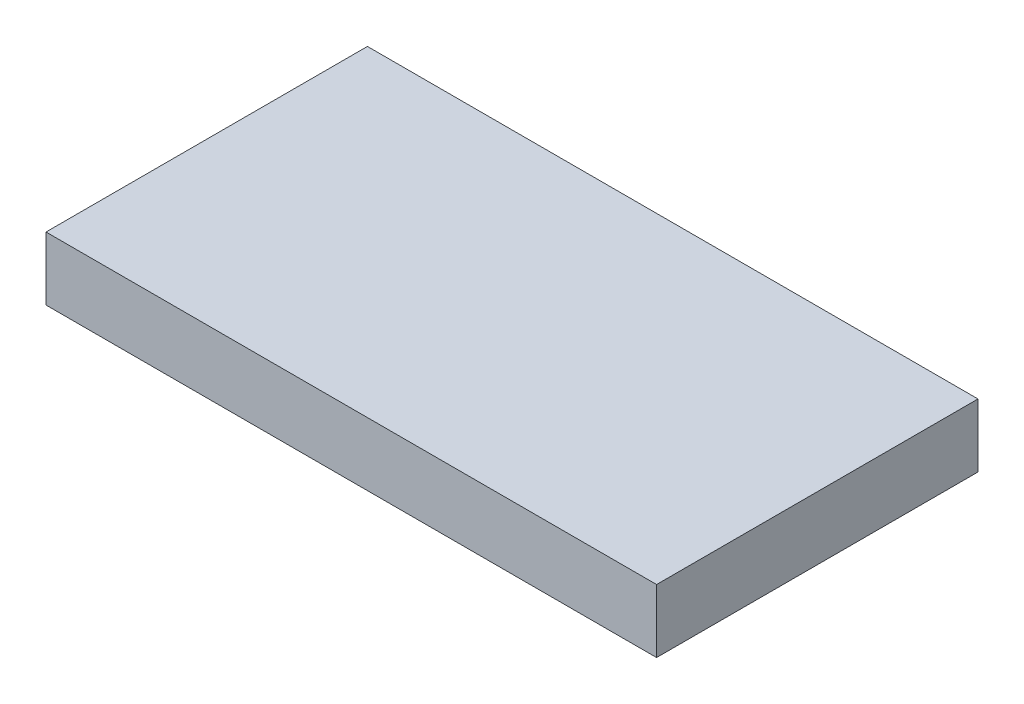
SolidWorks part; units mm, degrees
ref_plane "Front Plane" through (0, 0, 0) normal (0, 0, 1) x (1, 0, 0)
ref_plane "Top Plane" through (0, 0, 0) normal (0, 1, 0) x (1, 0, 0)
ref_plane "Right Plane" through (0, 0, 0) normal (1, 0, 0) x (0, 0, -1)
sketch "Sketch1" plane through (0, 0, 0) normal (0, 1, 0) x (1, 0, 0)
  line L1 (-482.5, 254) -> (482.5, 254)
  line L2 (-482.5, 254) -> (-482.5, -254)
  line L3 (-482.5, -254) -> (482.5, -254)
  line L4 (482.5, 254) -> (482.5, -254)
  line L5 (-482.5, 254) -> (482.5, -254) construction
  line L6 (-482.5, -254) -> (482.5, 254) construction
  point P0 (0, 0)
  dimension "D1" = 965
  dimension "D2" = 508
extrude "Boss-Extrude1" add sketch "Sketch1" along normal blind 100
sketch "Sketch2" plane through (0, 0, 254) normal (0, 0, 1) x (1, 0, 0)
  line L0 (-254, 50) -> (254, 50) construction
  line L1 (0, -55) -> (0, 55) construction
  line L2 (-482.5, 100) -> (482.5, 100) construction
  line L3 (-482.5, 0) -> (482.5, 0) construction
  circle A0 centre (-254, 50) radius 25
  circle A1 centre (254, 50) radius 25 construction
  point P4 (0, 50)
  dimension "D2" = 50
  dimension "D3" = 50
  dimension "D1" = 508
sketch "Sketch5" plane through (0, 0, 0) normal (0, -1, 0) x (1, 0, 0)
  line L0 (0, 0) -> (690.9122, 0) construction
  line L1 (55, 0) -> (-55, 0) construction
  line L2 (254, 204) -> (254, -204) construction
  line L3 (-482.5, 254) -> (482.5, 254) construction
  circle A0 centre (254, 204) radius 20
  circle A1 centre (254, -204) radius 20
  dimension "D1" = 50
extrude "Cut-Extrude1" cut sketch "Sketch5" against normal blind 50
mirror "Mirror1" about plane through (0, 0, 0) normal (1, 0, 0) of "Cut-Extrude1"
